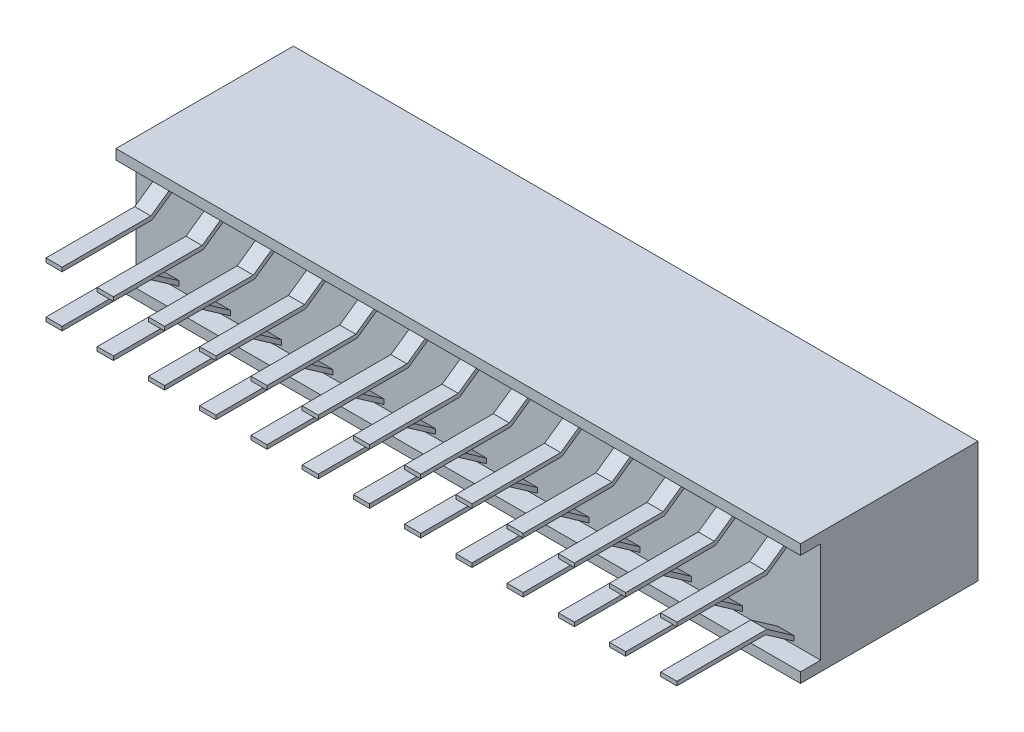
SolidWorks part; units mm, degrees
ref_plane "Front Plane" through (0, 0, 0) normal (0, 0, 1) x (1, 0, 0)
ref_plane "Top Plane" through (0, 0, 0) normal (0, 1, 0) x (1, 0, 0)
ref_plane "Right Plane" through (0, 0, 0) normal (1, 0, 0) x (0, 0, -1)
sketch "Sketch1" plane through (0, 0, 0) normal (0, 0, 1) x (1, 0, 0)
  line L1 (-8.485, -1.5) -> (8.485, -1.5)
  line L2 (-8.485, -1.5) -> (-8.485, 1.5)
  line L3 (-8.485, 1.5) -> (8.485, 1.5)
  line L4 (8.485, -1.5) -> (8.485, 1.5)
  line L5 (-8.485, -1.5) -> (8.485, 1.5) construction
  line L6 (-8.485, 1.5) -> (8.485, -1.5) construction
  point P0 (0, 0)
  dimension "D1" = 3
  dimension "D2" = 16.97
extrude "Boss-Extrude1" add sketch "Sketch1" along normal blind 4.4
sketch "Sketch3" plane through (0, 0, 0) normal (0, 0, -1) x (-1, 0, 0)
  line L0 (-8.485, -1.5) -> (-8.485, 1.5) construction
  line L1 (-7.845, 0.86) -> (-7.395, 0.86)
  line L2 (-7.845, 0.86) -> (-7.845, 0.41)
  line L3 (-7.845, 0.41) -> (-7.395, 0.41)
  line L4 (-7.395, 0.86) -> (-7.395, 0.41)
  line L5 (-7.845, 0.86) -> (-7.395, 0.41) construction
  line L6 (-7.845, 0.41) -> (-7.395, 0.86) construction
  line L7 (-7.845, -0.86) -> (-7.395, -0.86)
  line L8 (-7.845, -0.86) -> (-7.845, -0.41)
  line L9 (-7.845, -0.41) -> (-7.395, -0.41)
  line L10 (-7.395, -0.86) -> (-7.395, -0.41)
  line L11 (-7.845, -0.86) -> (-7.395, -0.41) construction
  line L12 (-7.845, -0.41) -> (-7.395, -0.86) construction
  line L13 (-8.485, 1.5) -> (8.485, 1.5) construction
  point P0 (-7.62, 0.635)
  point P5 (-7.62, -0.635)
  point P10 (0, 0)
  dimension "D1" = 0.865
  dimension "D2" = 0.865
  dimension "D3" = 1.27
  dimension "D4" = 0.45
extrude "Cut-Extrude1" cut sketch "Sketch3" against normal blind 3
chamfer "Chamfer1" distance 0.1 angle 45 8 edges at (7.845, -0.635, 0) (7.62, -0.41, 0) (7.62, -0.86, 0) (7.395, -0.635, 0) (7.62, 0.41, 0) (7.845, 0.635, 0) (7.62, 0.86, 0) (7.395, 0.635, 0)
sketch "Sketch4" plane through (8.485, 0, 0) normal (1, 0, 0) x (0, 0, -1)
  line L0 (-4.4, -1.5) -> (-4.4, 1.5) construction
  line L1 (-4.4, 1.25) -> (-3.9, 1.25)
  line L2 (-4.4, 1.25) -> (-4.4, -1.25)
  line L3 (-4.4, -1.25) -> (-3.9, -1.25)
  line L4 (-3.9, 1.25) -> (-3.9, -1.25)
  line L5 (0, 0) -> (-3.9, 0) construction
  line L6 (0, -1.5) -> (0, 1.5) construction
  dimension "D1" = 0.5
  dimension "D2" = 2.5
extrude "Cut-Extrude2" cut sketch "Sketch4" against normal through all
ref_plane "Plane1" through (7.62, 0, 0) normal (1, 0, 0) x (0, 0, -1)
sketch "Sketch5" plane through (7.62, 0, 0) normal (1, 0, 0) x (0, 0, -1)
  line L0 (-3.9, 1.1751) -> (-4.6, 0.685)
  line L1 (-3.9, -1.25) -> (-3.9, 1.25) construction
  line L2 (-4.6, 0.685) -> (-6.8, 0.685)
  line L3 (-6.8, 0.685) -> (-6.8, 0.585)
  line L4 (-6.8, 0.585) -> (-4.5685, 0.585)
  line L5 (-4.5685, 0.585) -> (-3.9, 1.0531)
  line L6 (-3.9, 1.0531) -> (-3.9, 1.1751)
  line L7 (-6.8, 0.635) -> (-6.8, 0) construction
  line L8 (-6.8, 0) -> (0, 0) construction
  line L9 (-4.4, 1.25) -> (-4.4, 1.5) construction
  dimension "D1" = 0.1
  dimension "D2" = 0.1
  dimension "D3" = 0.635
  dimension "D4" = 2.2
  dimension "D5" = 2.4
  dimension "D6" = 35
extrude "Boss-Extrude2" add sketch "Sketch5" along normal mid plane 0.4
mirror "Mirror1" about plane through (0, 0, 0) normal (0, 1, 0) of "Boss-Extrude2"
pattern_linear "LPattern1" count 13 spacing 1.27 along (-1, 0, 0) of "Mirror1", "Cut-Extrude1", "Chamfer1", "Boss-Extrude2"
